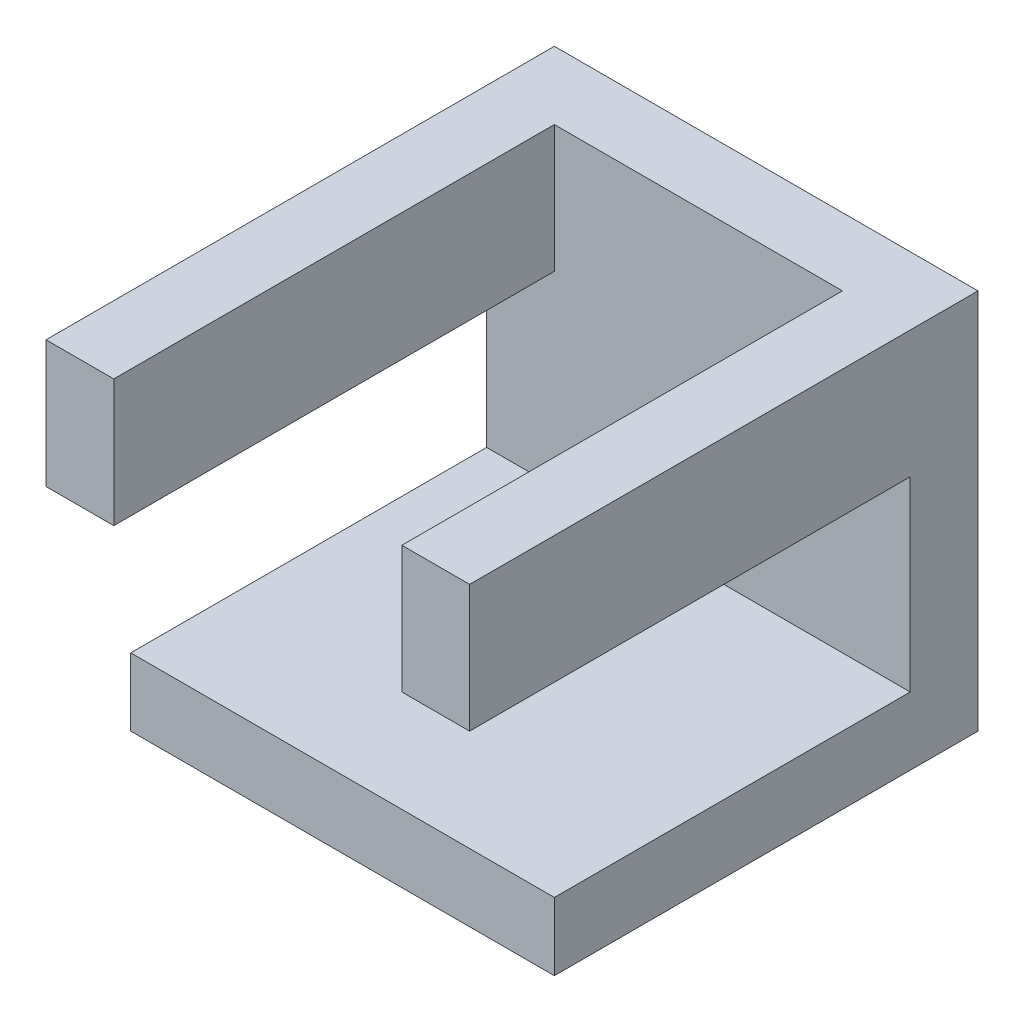
SolidWorks part; units mm, degrees
ref_plane "前视基准面" through (0, 0, 0) normal (0, 0, 1) x (1, 0, 0)
ref_plane "上视基准面" through (0, 0, 0) normal (0, 1, 0) x (1, 0, 0)
ref_plane "右视基准面" through (0, 0, 0) normal (1, 0, 0) x (0, 0, -1)
other "Configuration Table"
sketch "草图1" plane through (0, 0, 0) normal (0, 0, 1) x (1, 0, 0)
  line L1 (-250, -225) -> (250, -225)
  line L2 (-250, -225) -> (-250, 225)
  line L3 (-250, 225) -> (250, 225)
  line L4 (250, -225) -> (250, 225)
  line L5 (-250, -225) -> (250, 225) construction
  line L6 (-250, 225) -> (250, -225) construction
  point P0 (0, 0)
extrude "凸台-拉伸1" add sketch "草图1" along normal blind 80
sketch "草图2" plane through (0, 0, 0) normal (0, 0, 1) x (1, 0, 0)
  line L0 (250, -225) -> (250, 225) construction
  line L1 (-250, -225) -> (250, -225)
  line L2 (-250, -225) -> (-250, -145)
  line L3 (-250, -145) -> (250, -145)
  line L4 (250, -225) -> (250, -145)
  line L5 (-250, -225) -> (250, -145) construction
  line L6 (-250, -145) -> (250, -225) construction
  point P0 (0, -185)
extrude "凸台-拉伸2" add sketch "草图2" along normal blind 500
sketch "草图3" plane through (0, 0, 0) normal (0, 0, 1) x (1, 0, 0)
  line L0 (250, 225) -> (-250, 225) construction
  line L1 (-250, 75) -> (-170, 75)
  line L2 (-250, 75) -> (-250, 225)
  line L3 (-250, 225) -> (-170, 225)
  line L4 (-170, 75) -> (-170, 225)
  line L5 (-250, 75) -> (-170, 225) construction
  line L6 (-250, 225) -> (-170, 75) construction
  point P0 (-210, 150)
extrude "凸台-拉伸3" add sketch "草图3" along normal blind 600
sketch "草图4" plane through (0, 0, 0) normal (0, 0, 1) x (1, 0, 0)
  line L1 (170, 75) -> (250, 75)
  line L2 (170, 75) -> (170, 225)
  line L3 (170, 225) -> (250, 225)
  line L4 (250, 75) -> (250, 225)
  line L5 (170, 75) -> (250, 225) construction
  line L6 (170, 225) -> (250, 75) construction
  point P0 (210, 150)
extrude "凸台-拉伸4" add sketch "草图4" along normal blind 600
